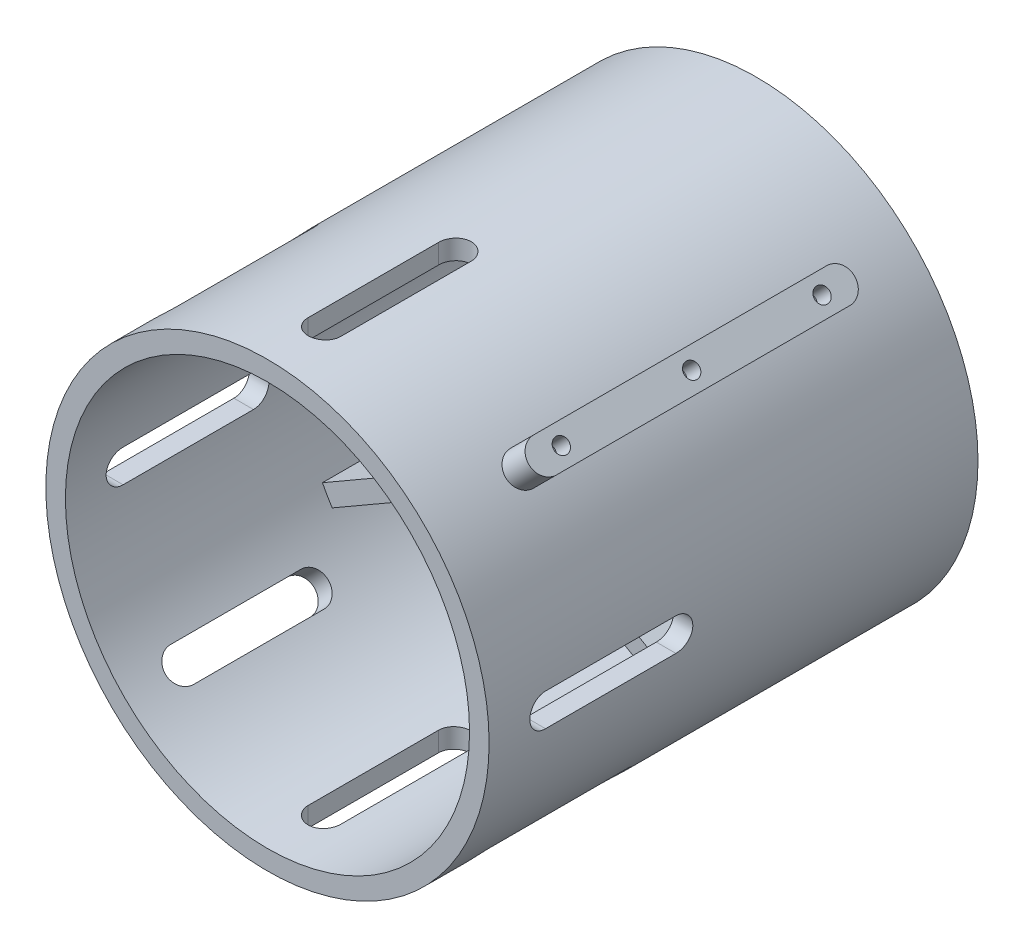
SolidWorks part; units mm, degrees
material "Polyethylene Cross-Linked"
ref_plane "Front Plane" through (0, 0, 0) normal (0, 0, 1) x (1, 0, 0)
ref_plane "Top Plane" through (0, 0, 0) normal (0, 1, 0) x (1, 0, 0)
ref_plane "Right Plane" through (0, 0, 0) normal (1, 0, 0) x (0, 0, -1)
sketch "Sketch2" plane through (0, 0, 0) normal (0, 0, 1) x (1, 0, 0)
  circle A0 centre (0, 0) radius 31
  circle A1 centre (0, 0) radius 34
  dimension "D1" = 62
  dimension "D2" = 3
extrude "Boss-Extrude1" add sketch "Sketch2" along normal blind 75
ref_plane "Plane1" through (0, 0, 37.5) normal (0, 0, 1) x (1, 0, 0)
sketch "Sketch3" plane through (0, 0, 37.5) normal (0, 0, 1) x (1, 0, 0)
  line L0 (0, 0) -> (26.8468, -15.5) construction
  line L1 (0, 0) -> (0, 31) construction
  line L2 (-1.5, 30.9637) -> (-1.5, 14.9248)
  line L3 (1.5, 30.9637) -> (1.5, 14.9248)
  line L4 (26.8468, -15.5) -> (27.5968, -14.201) construction
  line L5 (27.5968, -14.201) -> (13.6753, -6.1634)
  line L6 (26.0968, -16.799) -> (12.1753, -8.7614)
  line L7 (0, 0) -> (-26.8468, -15.5) construction
  line L8 (-26.8468, -15.5) -> (-27.5968, -14.201) construction
  line L9 (-27.5968, -14.201) -> (-13.6753, -6.1634)
  line L10 (-26.0968, -16.799) -> (-12.1753, -8.7614)
  circle A1 centre (0, 0) radius 12
  circle A2 centre (0, 0) radius 31 construction
  arc A3 (-1.5, 30.9637) -> (1.5, 30.9637) centre (0, 0) cw
  arc A4 (27.5968, -14.201) -> (26.0968, -16.799) centre (0, 0) cw
  arc A5 (-27.5968, -14.201) -> (-26.0968, -16.799) centre (0, 0) ccw
  arc A6 (1.5, 14.9248) -> (13.6753, -6.1634) centre (0, 0) cw
  arc A7 (-1.5, 14.9248) -> (-13.6753, -6.1634) centre (0, 0) ccw
  arc A8 (12.1753, -8.7614) -> (-12.1753, -8.7614) centre (0, 0) cw
  dimension "D3" = 120
  dimension "D5" = 120
  dimension "D4" = 1.5
  dimension "D6" = 1.5
extrude "Boss-Extrude2" add sketch "Sketch3" along normal blind 1.5 and the other way blind 30 contours A8 L6 A4 L5 A6 L3 A3 L2 A7 L9 A5 L10 A1
ref_plane "Plane2" through (34, 0, 0) normal (1, 0, 0) x (0, 0, -1)
sketch "Sketch5" plane through (34, 0, 0) normal (1, 0, 0) x (0, 0, -1)
  line L0 (-75, 0) -> (0, 0) construction
  line L1 (-75, 34) -> (-75, -34) construction
  line L2 (-75, 0) -> (-66.25, 0) construction
  line L3 (-37.5, 0) -> (-46.25, 0) construction
  line L4 (-66.25, 0) -> (-46.25, 0) construction
  line L5 (-66.25, 2.5) -> (-46.25, 2.5)
  line L6 (-66.25, -2.5) -> (-46.25, -2.5)
  arc A0 (-66.25, 2.5) -> (-66.25, -2.5) centre (-66.25, 0) ccw
  arc A1 (-46.25, -2.5) -> (-46.25, 2.5) centre (-46.25, 0) ccw
  point P8 (-56.25, 0)
  dimension "D1" = 8.75
  dimension "D2" = 8.75
  dimension "D3" = 5
extrude "Cut-Extrude2" cut sketch "Sketch5" against normal up to next
pattern_circular "CirPattern1" count 7 every 45 about axis through (0, 0, 0) along (0, 0, 1) of "Cut-Extrude2"
ref_plane "Plane3" through (24.0416, 24.0416, 0) normal (0.7071, 0.7071, 0) x (0, 0, -1)
sketch "Sketch6" plane through (24.0416, 24.0416, 0) normal (0.7071, 0.7071, 0) x (0, 0, -1)
  line L0 (-75, 0) -> (0, 0) construction
  line L1 (-75, 34) -> (-75, -34) construction
  line L2 (-37.5, 0) -> (-60, 0) construction
  line L3 (-37.5, 37.4) -> (-37.5, -37.4) construction
  line L4 (-37.5, 0) -> (-15, 0) construction
  line L5 (-60, 0) -> (-15, 0) construction
  line L6 (-60, 2.5) -> (-15, 2.5)
  line L7 (-60, -2.5) -> (-15, -2.5)
  line L8 (-38.65, 0) -> (-57.5, 0) construction
  arc A0 (-60, 2.5) -> (-60, -2.5) centre (-60, 0) ccw
  arc A1 (-15, -2.5) -> (-15, 2.5) centre (-15, 0) ccw
  circle A2 centre (-37.5, 0) radius 1.15
  circle A3 centre (-57.5, 0) radius 1.15
  circle A4 centre (-17.5, 0) radius 1.15
  point P7 (-37.5, 0)
  point P11 (-15, 0)
  dimension "D3" = 2.3
  dimension "D5" = 2.3
  dimension "D1" = 22.5
  dimension "D2" = 5
  dimension "D4" = 20
extrude "Boss-Extrude4" add sketch "Sketch6" along normal blind 5 separate body
sketch "Sketch7" plane through (24.0416, 24.0416, 0) normal (0.7071, 0.7071, 0) x (0, 0, -1)
  circle A0 centre (-57.5, 0) radius 1.15
  circle A1 centre (-37.5, 0) radius 1.15
  circle A2 centre (-17.5, 0) radius 1.15
extrude "Boss-Extrude5" add sketch "Sketch7" along normal blind 2
